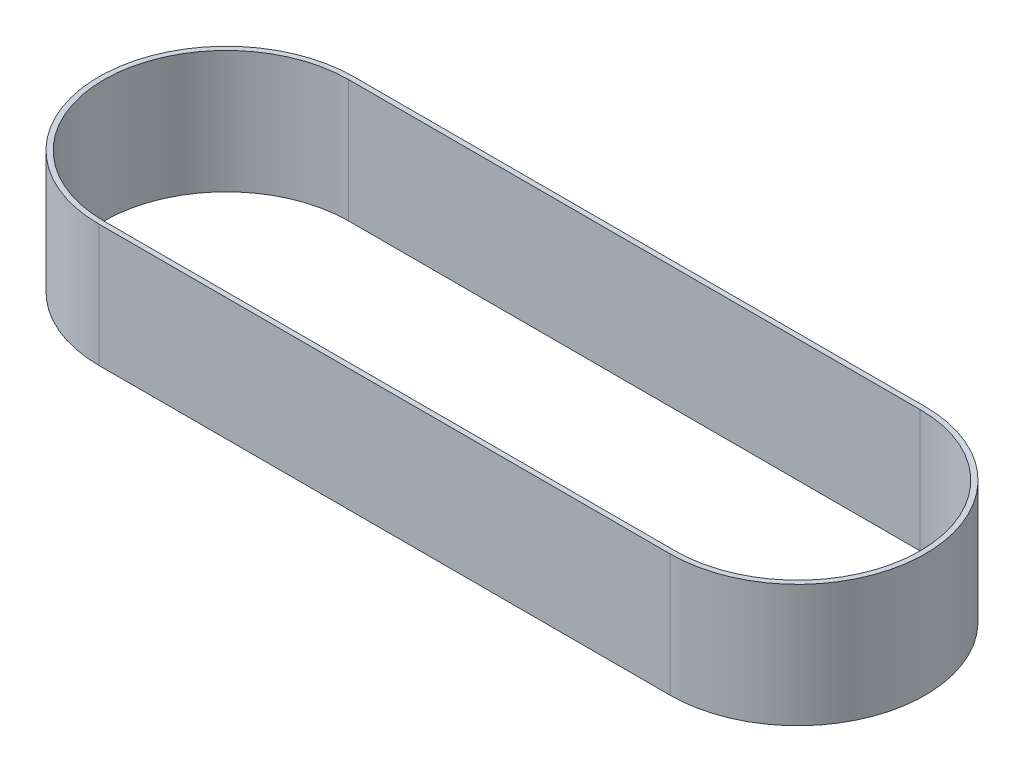
SolidWorks part; units mm, degrees
material "EPDM 60 Durometer"
ref_plane "Ebene vorne" through (0, 0, 0) normal (0, 0, 1) x (1, 0, 0)
ref_plane "Ebene oben" through (0, 0, 0) normal (0, 1, 0) x (1, 0, 0)
ref_plane "Ebene rechts" through (0, 0, 0) normal (1, 0, 0) x (0, 0, -1)
sketch "Skizze3" plane through (0, 0, 0) normal (0, 1, 0) x (1, 0, 0)
  line L1 (-700, -312.5) -> (700, -312.5)
  line L2 (-700, -312.5) -> (-700, 312.5)
  line L3 (-700, 312.5) -> (700, 312.5)
  line L4 (700, -312.5) -> (700, 312.5)
  line L5 (-700, -312.5) -> (700, 312.5) construction
  line L6 (-700, 312.5) -> (700, -312.5) construction
  point P0 (0, 0)
  dimension "D1" = 1400
  dimension "D2" = 625
extrude "Aufsatz-Linear austragen1" add sketch "Skizze3" along normal blind 300
sketch "Skizze4" plane through (0, 0, 0) normal (0, 1, 0) x (1, 0, 0)
  line L0 (-700, 312.5) -> (-700, -312.5) construction
  circle A0 centre (-700, 0) radius 312.5
extrude "Aufsatz-Linear austragen2" add sketch "Skizze4" along normal up to surface (300 mm away) up to face at (0, 300, 0)
mirror "Spiegeln1" about plane through (0, 0, 0) normal (1, 0, 0) of "Aufsatz-Linear austragen2"
sketch "Skizze5" plane through (0, 300, 0) normal (0, 1, 0) x (1, 0, 0)
  line L1 (700, 300) -> (-700, 300)
  line L2 (700, 300) -> (700, -300)
  line L3 (700, -300) -> (-700, -300)
  line L4 (-700, 300) -> (-700, -300)
  line L5 (700, 300) -> (-700, -300) construction
  line L6 (700, -300) -> (-700, 300) construction
  point P0 (0, 0)
  dimension "D1" = 1400
  dimension "D2" = 600
extrude "Schnitt-Linear austragen1" cut sketch "Skizze5" against normal through all
sketch "Skizze6" plane through (0, 300, 0) normal (0, 1, 0) x (1, 0, 0)
  line L0 (-700, 300) -> (-700, -300) construction
  circle A0 centre (-700, 0) radius 300
extrude "Schnitt-Linear austragen2" cut sketch "Skizze6" against normal through all
mirror "Spiegeln2" about plane through (0, 0, 0) normal (1, 0, 0) of "Schnitt-Linear austragen2"
